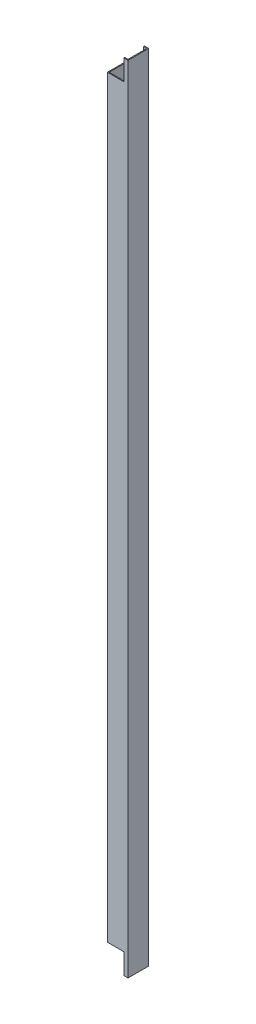
SolidWorks part; units mm, degrees
ref_plane "Front Plane" through (0, 0, 0) normal (0, 0, 1) x (1, 0, 0)
ref_plane "Top Plane" through (0, 0, 0) normal (0, 1, 0) x (1, 0, 0)
ref_plane "Right Plane" through (0, 0, 0) normal (1, 0, 0) x (0, 0, -1)
sketch "Sketch1" plane through (0, 0, 0) normal (0, 1, 0) x (1, 0, 0)
  line L0 (0, 0) -> (0, 50)
  line L1 (0, 50) -> (50, 50)
  line L2 (50, 50) -> (50, 0)
  line L3 (50, 0) -> (0, 0)
  line L4 (2.2, 47.8) -> (47.8, 47.8)
  line L5 (47.8, 47.8) -> (47.8, 2.2)
  line L6 (47.8, 2.2) -> (2.2, 2.2)
  line L7 (2.2, 2.2) -> (2.2, 47.8)
  dimension "D1" = 50
  dimension "D2" = 50
  dimension "D3" = 2.2
extrude "Boss-Extrude1" add sketch "Sketch1" along normal blind 1923
sketch "Sketch2" plane through (0, 0, 0) normal (0, 0, 1) x (1, 0, 0)
  line L0 (0, 0) -> (0, 50)
  line L1 (0, 1923) -> (0, 0) construction
  line L2 (0, 50) -> (40, 50)
  line L3 (40, 50) -> (40, 0)
  line L5 (40, 0) -> (0, 0)
  line L6 (0, 1923) -> (40, 1923)
  line L7 (0, 1923) -> (50, 1923) construction
  line L8 (40, 1923) -> (40, 1873)
  line L9 (40, 1873) -> (0, 1873)
  line L10 (0, 1873) -> (0, 1923)
  dimension "D1" = 50
  dimension "D2" = 40
  dimension "D3" = 50
  dimension "D4" = 40
extrude "Cut-Extrude2" cut sketch "Sketch2" against normal blind 50
equation "\"SquareTube_length\"=1923.0"
equation "\"D1@Boss-Extrude1\"=\"SquareTube_length\""
equation "\"SquareTube_inBack1_cutDepth50_R\"=50"
equation "\"D1@Sketch2\" = \"SquareTube_inBack4_cutDepth50_R\""
equation "\"SquareTube_inBack1_cutDepth50_L\"=50"
equation "\"D3@Sketch2\" = \"SquareTube_inBack4_cutDepth50_L\""
equation "\"CarBeamWidth\"=700.0"
equation "\"MetalSheet_3mm_length\"=5030.0"
equation "\"MetalSheet_3mm_width\"=1923.0"
equation "\"MetalSheet_3mm_FloorCut_L_length\"=1764.0"
equation "\"MetalSheet_3mm_FloorCut_L_disdance\"=1665.0"
equation "\"MetalSheet_3mm_FloorCut_R_length\"=1764.0"
equation "\"MetalSheet_3mm_FloorCut_R_disdance\"=1665.0"
equation "\"indoorHeight\"=1940.0"
equation "\"x\"=66.0"
equation "\"da\"=62.0"
equation "\"SquareTube_wheel_length\"= 750"
equation "\"channelSteel_length\"=5030.0"
equation "\"SquareTube_inFront1_cutDepth50_R\"=0.5"
equation "\"SquareTube_inFront1_cutDepth50_L\"=0.5"
equation "\"SquareTube_inFront2_cutDepth50_R\"=0.5"
equation "\"SquareTube_inFront2_cutDepth50_L\"=0.5"
equation "\"SquareTube_inFront3_cutDepth50_R\"=0.5"
equation "\"SquareTube_inFront3_cutDepth50_L\"=0.5"
equation "\"SquareTube_inFront4_cutDepth50_R\"=0.5"
equation "\"SquareTube_inFront4_cutDepth50_L\"=0.5"
equation "\"SquareTube_inFront5_cutDepth50_R\"=50"
equation "\"SquareTube_inFront5_cutDepth50_L\"=50"
equation "\"SquareTube_inFront6_cutDepth50_R\"=50"
equation "\"SquareTube_inFront6_cutDepth50_L\"=50"
equation "\"SquareTube_inFront7_cutDepth50_R\"=50"
equation "\"SquareTube_inFront7_cutDepth50_L\"=50"
equation "\"SquareTube_inFront8_cutDepth50_R\"=50"
equation "\"SquareTube_inFront8_cutDepth50_L\"=50"
equation "\"SquareTube_inFront9_cutDepth50_R\"=50"
equation "\"SquareTube_inFront9_cutDepth50_L\"=50"
equation "\"SquareTube_inFront10_cutDepth50_R\"=50"
equation "\"SquareTube_inFront10_cutDepth50_L\"=50"
equation "\"SquareTube_inBack2_cutDepth50_R\"=50"
equation "\"SquareTube_inBack2_cutDepth50_L\"=50"
equation "\"SquareTube_inBack3_cutDepth50_R\"=50"
equation "\"SquareTube_inBack3_cutDepth50_L\"=50"
equation "\"SquareTube_inBack4_cutDepth50_R\"=50"
equation "\"SquareTube_inBack4_cutDepth50_L\"=50"
equation "\"SquareTube_inBack5_cutDepth50_R\"=50"
equation "\"SquareTube_inBack5_cutDepth50_L\"=50"
equation "\"SquareTube_inBack6_cutDepth50_R\"=0.5"
equation "\"SquareTube_inBack6_cutDepth50_L\"=0.5"
equation "\"SquareTube_inFront11_cutDepth50_R\"=50"
equation "\"SquareTube_inFront11_cutDepth50_L\"=50"
equation "\"SquareTube_inFront12_cutDepth50_R\"=50"
equation "\"SquareTube_inFront12_cutDepth50_L\"=50"
equation "\"SquareTube_inFront13_cutDepth50_R\"=50"
equation "\"SquareTube_inFront13_cutDepth50_L\"=50"
equation "\"SquareTube_inFront14_cutDepth50_R\"=50"
equation "\"SquareTube_inFront14_cutDepth50_L\"=50"
equation "\"SquareTube_inBack7_cutDepth50_R\"=0.5"
equation "\"SquareTube_inBack7_cutDepth50_L\"=0.5"
equation "\"SquareTube_inBack8_cutDepth50_R\"=0.5"
equation "\"SquareTube_inBack8_cutDepth50_L\"=0.5"
